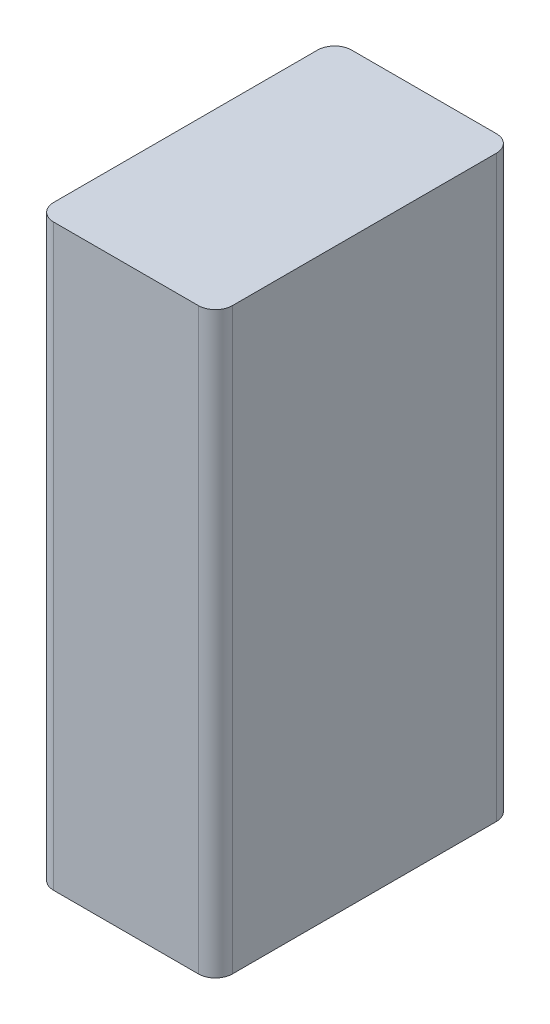
SolidWorks part; units mm, degrees
ref_plane "Front Plane" through (0, 0, 0) normal (0, 0, 1) x (1, 0, 0)
ref_plane "Top Plane" through (0, 0, 0) normal (0, 1, 0) x (1, 0, 0)
ref_plane "Right Plane" through (0, 0, 0) normal (1, 0, 0) x (0, 0, -1)
sketch "Sketch1" plane through (0, 0, 0) normal (0, 1, 0) x (1, 0, 0)
  line L1 (0, 0) -> (21, 0)
  line L2 (0, 0) -> (0, 35)
  line L3 (0, 35) -> (21, 35)
  line L4 (21, 0) -> (21, 35)
  dimension "D1" = 21
  dimension "D2" = 35
extrude "Boss-Extrude1" add sketch "Sketch1" along normal blind 68
fillet "Fillet1" radius 2 4 edges at (0, 34, -35) (21, 34, -35) (0, 34, 0) (21, 34, 0)
